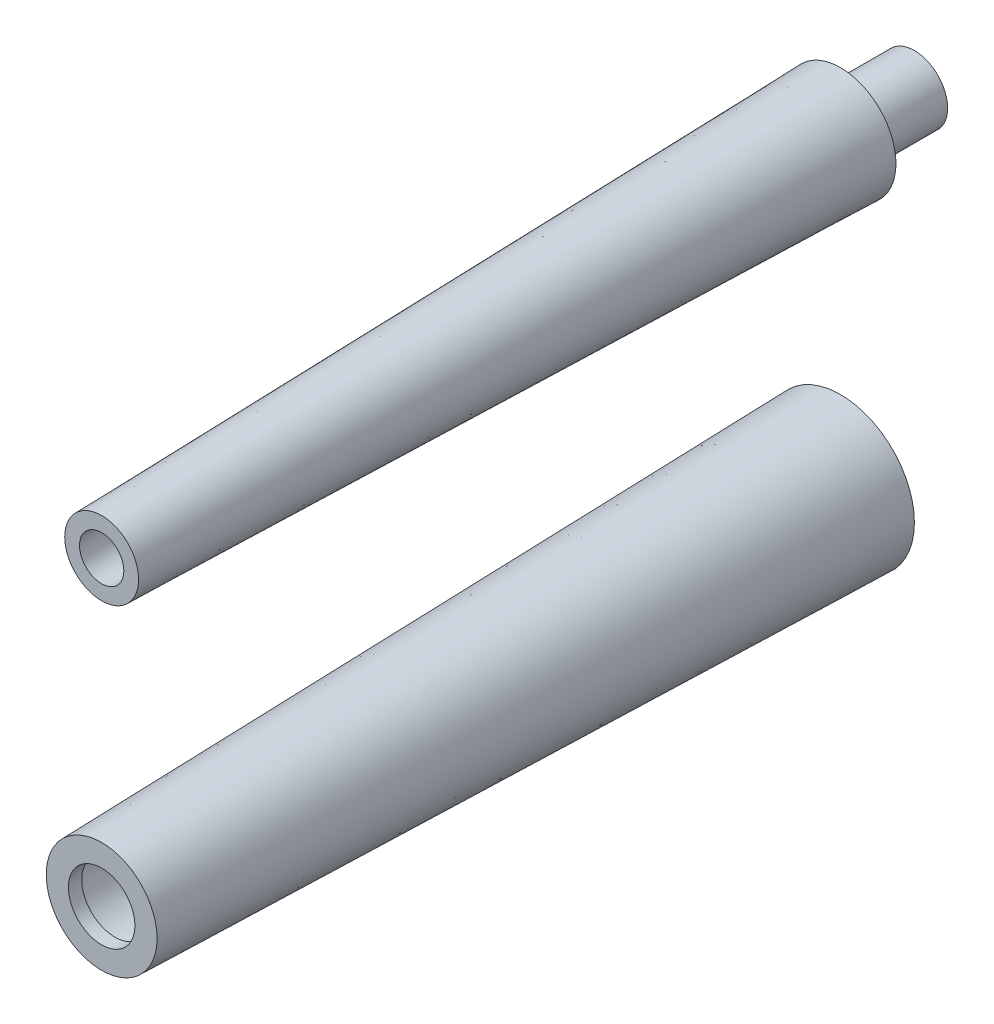
SolidWorks part; units mm, degrees
ref_plane "Top" through (0, 0, 0) normal (0, 0, 1) x (1, 0, 0)
ref_plane "Front" through (0, 0, 0) normal (0, 1, 0) x (1, 0, 0)
ref_plane "Right" through (0, 0, 0) normal (1, 0, 0) x (0, 0, -1)
sketch "Sketch1" plane through (0, 0, 0) normal (0, 0, 1) x (1, 0, 0)
  line L2 (0, -50) -> (0, 50) construction
  circle A0 centre (0, -25.1228) radius 10
  circle A1 centre (0, 15.7017) radius 7.5
  dimension "D1" = 20
  dimension "D2" = 15
extrude "Boss-Extrude1" add sketch "Sketch1" along normal blind 100
sketch "Sketch2" plane through (0, 0, 0) normal (1, 0, 0) x (0, 0, -1)
  line L0 (-100, -17.6228) -> (0, -15.1228)
  line L1 (-100, -15.1228) -> (-100, -35.1228) construction
  line L2 (0, -15.1228) -> (-100, -15.1228) construction
  line L3 (-100, -25.1228) -> (0, -25.1228) construction
  line L4 (0, -35.1228) -> (0, -15.1228) construction
  line L5 (-100, -17.6228) -> (-101.8146, -12.6504)
  line L6 (-101.8146, -12.6504) -> (0, -12.6504)
  line L7 (0, -12.6504) -> (0, -15.1228)
  dimension "D1" = 2.5
revolve "Cut-Revolve1" cut sketch "Sketch2" angle 360 about L3
sketch "Sketch3" plane through (0, 0, 0) normal (1, 0, 0) x (0, 0, -1)
  line L0 (0, 8.2017) -> (-100, 10.7017)
  line L1 (-100, 23.2017) -> (-100, 8.2017) construction
  line L2 (-100, 10.7017) -> (-103.6483, 0.6999)
  line L3 (-103.6483, 0.6999) -> (0, 5.7008)
  line L4 (0, 5.7008) -> (0, 8.2017)
  line L5 (-100, 8.2017) -> (0, 8.2017) construction
  line L6 (0, 15.7017) -> (-100, 15.7017) construction
  line L7 (0, 8.2017) -> (0, 23.2017) construction
  dimension "D1" = 2.5
revolve "Cut-Revolve2" cut sketch "Sketch3" angle 360 about L6
shell "Shell1" thickness 1.8
shell "Shell2" thickness 2
sketch "Sketch4" plane through (0, 0, 0) normal (0, 0, -1) x (-1, 0, 0)
  circle A0 centre (0, 15.7017) radius 4
  dimension "D1" = 8
extrude "Cut-Extrude1" cut sketch "Sketch4" against normal mid plane 10
sketch "Sketch5" plane through (0, 0, 100) normal (0, 0, 1) x (1, 0, 0)
  circle A0 centre (0, -25.1228) radius 4.5
  dimension "D1" = 9
extrude "Cut-Extrude2" cut sketch "Sketch5" against normal blind 10
sketch "Sketch6" plane through (0, 0, 0) normal (0, 0, -1) x (-1, 0, 0)
  circle A3 centre (0, 15.7017) radius 4.5
  circle A4 centre (0, 15.7017) radius 4
  dimension "D1" = 9
  dimension "D2" = 8
extrude "Boss-Extrude2" add sketch "Sketch6" along normal blind 10
ref_plane "Plane1" [suppressed] through (0, 0, 5) normal (0, 0, -1) x (-1, 0, 0)
